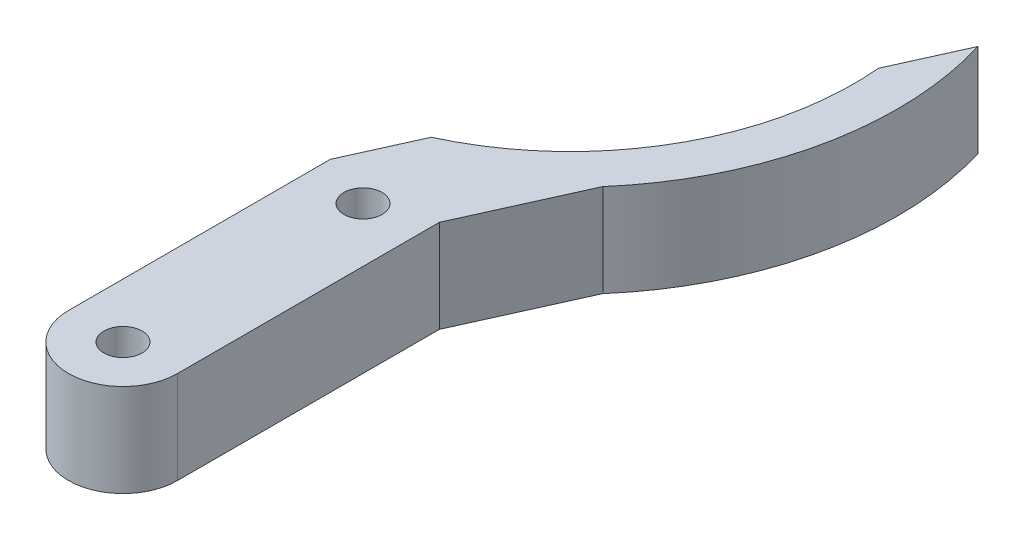
SolidWorks part; units mm, degrees
ref_plane "前视基准面" through (0, 0, 0) normal (0, 0, 1) x (1, 0, 0)
ref_plane "上视基准面" through (0, 0, 0) normal (0, 1, 0) x (1, 0, 0)
ref_plane "右视基准面" through (0, 0, 0) normal (1, 0, 0) x (0, 0, -1)
sketch "草图1" plane through (0, 0, 0) normal (0, 1, 0) x (1, 0, 0)
  line L2 (-5, 0) -> (-5, 24)
  line L4 (5, 0) -> (5, 24)
  line L6 (12.8934, 56.3523) -> (15.727, 62.6464)
  line L7 (5, 24) -> (9.6496, 34.3278)
  line L8 (-5, 24) -> (-2.1264, 30.383)
  circle A0 centre (0, 0) radius 1.75
  circle A1 centre (0, 22) radius 1.75
  arc A2 (9.6496, 34.3278) -> (15.727, 62.6464) centre (-13, 54) ccw
  arc A3 (-2.1264, 30.383) -> (12.8934, 56.3523) centre (-13, 54) ccw
  arc A6 (5, 0) -> (-5, 0) centre (0, 0) cw
  point P29 (0, 0)
  point P32 (10, 0)
  dimension "D3" = 3.5
  dimension "D4" = 22
  dimension "D5" = 30
  dimension "D6" = 26
  dimension "D10" = 10
  dimension "D1" = 10
  dimension "D2" = 24
  dimension "D7" = 8
  dimension "D8" = 7
  dimension "D9" = 32
  dimension "D11" = 30
  dimension "D12" = 24
extrude "凸台-拉伸1" add sketch "草图1" along normal blind 8.5
